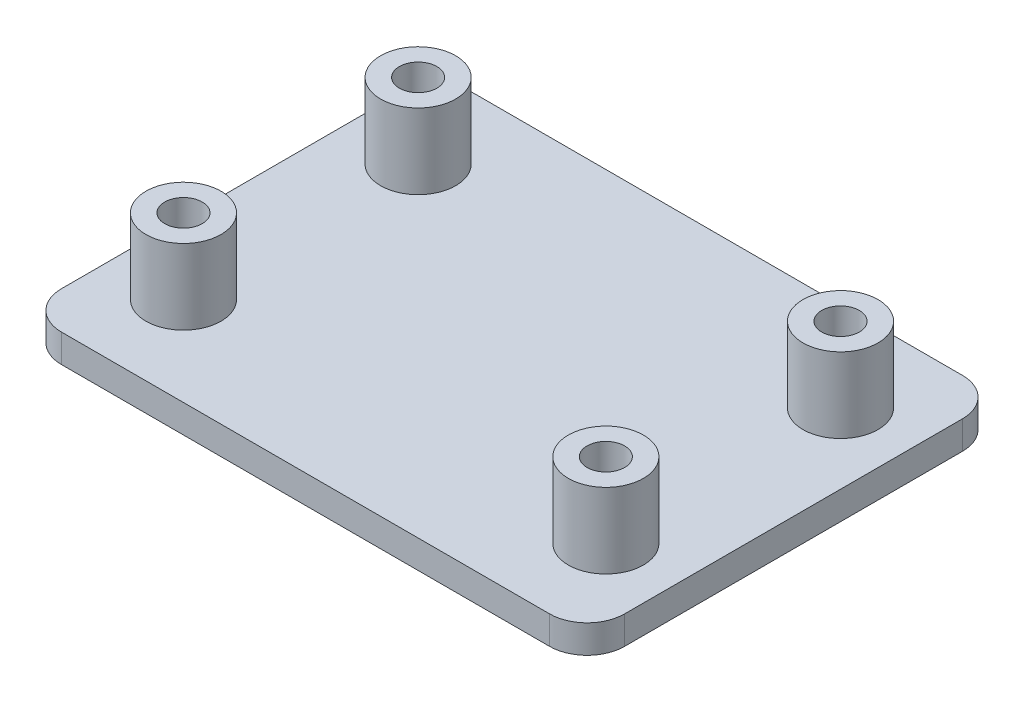
SolidWorks part; units mm, degrees
ref_plane "Front Plane" through (0, 0, 0) normal (0, 0, 1) x (1, 0, 0)
ref_plane "Top Plane" through (0, 0, 0) normal (0, 1, 0) x (1, 0, 0)
ref_plane "Right Plane" through (0, 0, 0) normal (1, 0, 0) x (0, 0, -1)
sketch "Sketch1" plane through (0, 0, 0) normal (0, 1, 0) x (1, 0, 0)
  line L0 (-26, -22) -> (26, -22)
  line L1 (30, -18) -> (30, 18)
  line L2 (26, 22) -> (-26, 22)
  line L3 (-30, 18) -> (-30, -18)
  arc A0 (26, -22) -> (30, -18) centre (26, -18) ccw
  arc A1 (30, 18) -> (26, 22) centre (26, 18) ccw
  arc A2 (-26, 22) -> (-30, 18) centre (-26, 18) ccw
  arc A3 (-30, -18) -> (-26, -22) centre (-26, -18) ccw
extrude "Boss-Extrude1" add sketch "Sketch1" along normal blind 3
ref_plane "Plane1" through (0, 3, 0) normal (0, 1, 0) x (1, 0, 0)
sketch "Sketch2" plane through (0, 3, 0) normal (0, 1, 0) x (1, 0, 0)
  circle A0 centre (22.5, -12.5) radius 4
  circle A1 centre (22.5, 12.5) radius 4
  circle A2 centre (-22.5, -12.5) radius 4
  circle A3 centre (-22.5, 12.5) radius 4
extrude "Boss-Extrude2" add sketch "Sketch2" along normal blind 8
ref_plane "Plane2" through (0, 11, 0) normal (0, 1, 0) x (1, 0, 0)
sketch "Sketch3" plane through (0, 11, 0) normal (0, 1, 0) x (1, 0, 0)
  circle A0 centre (22.5, -12.5) radius 2
  circle A1 centre (22.5, 12.5) radius 2
  circle A2 centre (-22.5, -12.5) radius 2
  circle A3 centre (-22.5, 12.5) radius 2
extrude "Cut-Extrude1" cut sketch "Sketch3" against normal blind 7
